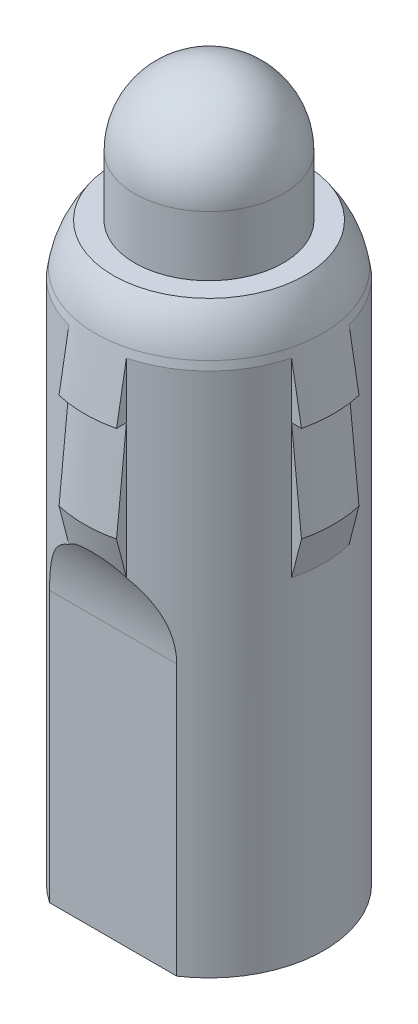
SolidWorks part; units mm, degrees
ref_plane "Front Plane" through (0, 0, 0) normal (0, 0, 1) x (1, 0, 0)
ref_plane "Top Plane" through (0, 0, 0) normal (0, 1, 0) x (1, 0, 0)
ref_plane "Right Plane" through (0, 0, 0) normal (1, 0, 0) x (0, 0, -1)
sketch "Sketch2" plane through (0, 0, 0) normal (0, 0, 1) x (1, 0, 0)
  line L0 (0, 0) -> (0, 50.7036) construction
  line L1 (0, 0) -> (30.811, 0) construction
  line L2 (0, 0) -> (6, 0)
  line L3 (6, 0) -> (6, 17.5)
  line L4 (3.875, 30) -> (5, 30)
  line L5 (3.875, 30) -> (3.875, 33.125)
  line L6 (0, 37) -> (0, 0)
  line L7 (6, 17.5) -> (6.5, 19.5)
  line L8 (6.5, 19.5) -> (6, 24.5)
  line L9 (6, 24.5) -> (6.5, 24.5)
  line L10 (6.5, 24.5) -> (5.9285, 27.8427)
  arc A0 (5.9285, 27.8427) -> (5, 30) centre (1, 27) ccw
  arc A1 (3.875, 33.125) -> (0, 37) centre (0, 33.125) ccw
  dimension "D1" = 3.875
  dimension "D5" = 5
  dimension "D6" = 5
  dimension "D2" = 30
  dimension "D3" = 3.125
  dimension "D4" = 6
  dimension "D7" = 17.5
  dimension "D8" = 19.5
  dimension "D9" = 24.5
  dimension "D10" = 6.5
revolve "Revolve1" add sketch "Sketch2" angle 360 about L6
sketch "Sketch3" plane through (0, 0, 0) normal (0, -1, 0) x (1, 0, 0)
  line L0 (0, 0) -> (0, 7.4955) construction
  line L1 (0, 0) -> (-7.2703, 0) construction
  line L2 (-5.8095, 1.5) -> (-7.5797, 1.5)
  line L3 (-7.5797, 1.5) -> (-7.5797, 7.4955)
  line L4 (-7.5797, 7.4955) -> (-1.5, 7.4955)
  line L5 (-1.5, 7.4955) -> (-1.5, 5.8095)
  line L6 (1.5, 7.4955) -> (1.5, 5.8095)
  line L7 (7.5797, 7.4955) -> (1.5, 7.4955)
  line L8 (7.5797, 1.5) -> (7.5797, 7.4955)
  line L9 (5.8095, 1.5) -> (7.5797, 1.5)
  line L10 (5.8095, -1.5) -> (7.5797, -1.5)
  line L11 (7.5797, -1.5) -> (7.5797, -7.4955)
  line L12 (7.5797, -7.4955) -> (1.5, -7.4955)
  line L13 (1.5, -7.4955) -> (1.5, -5.8095)
  line L14 (-1.5, -7.4955) -> (-1.5, -5.8095)
  line L15 (-7.5797, -7.4955) -> (-1.5, -7.4955)
  line L16 (-7.5797, -1.5) -> (-7.5797, -7.4955)
  line L17 (-5.8095, -1.5) -> (-7.5797, -1.5)
  arc A1 (-1.5, 5.8095) -> (-5.8095, 1.5) centre (0, 0) ccw
  circle A2 centre (0, 0) radius 6 construction
  circle A3 centre (0, 0) radius 6 construction
  arc A4 (1.5, 5.8095) -> (5.8095, 1.5) centre (0, 0) cw
  arc A5 (1.5, -5.8095) -> (5.8095, -1.5) centre (0, 0) ccw
  arc A6 (-1.5, -5.8095) -> (-5.8095, -1.5) centre (0, 0) cw
  dimension "D1" = 3
  dimension "D2" = 3
extrude "Cut-Extrude1" cut sketch "Sketch3" against normal through all
sketch "Sketch4" plane through (0, 0, 0) normal (1, 0, 0) x (0, 0, -1)
  line L0 (-5, 0) -> (-5, 14.1108)
  line L1 (-6, 0) -> (6, 0) construction
  line L2 (-12.5, 21.6108) -> (-12.5, 0)
  line L3 (-12.5, 0) -> (-5, 0)
  line L5 (0, 0) -> (0, 38.6978) construction
  line L6 (12.5, 0) -> (5, 0)
  line L7 (12.5, 21.6108) -> (12.5, 0)
  line L8 (5, 0) -> (5, 14.1108)
  arc A0 (-5, 14.1108) -> (-12.5, 21.6108) centre (-12.5, 14.1108) ccw
  arc A1 (5, 14.1108) -> (12.5, 21.6108) centre (12.5, 14.1108) cw
  dimension "D2" = 7.5
  dimension "D1" = 5
extrude "Cut-Extrude2" cut sketch "Sketch4" against normal mid plane 20
